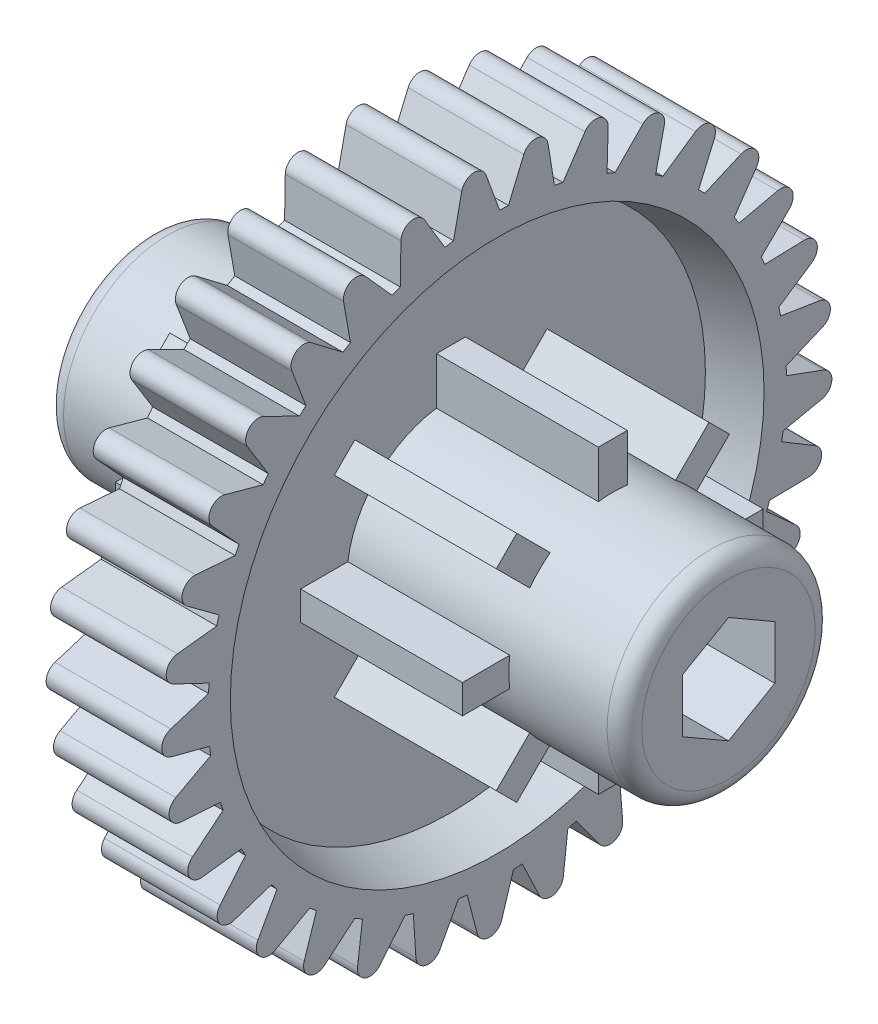
SolidWorks part; units mm, degrees
ref_plane "Front Plane" through (0, 0, 0) normal (0, 0, 1) x (1, 0, 0)
ref_plane "Top Plane" through (0, 0, 0) normal (0, 1, 0) x (1, 0, 0)
ref_plane "Right Plane" through (0, 0, 0) normal (1, 0, 0) x (0, 0, -1)
sketch "Sketch1" plane through (0, 0, 0) normal (1, 0, 0) x (0, 0, -1)
  line L1 (0, -2.3094) -> (2, -1.1547)
  line L2 (2, -1.1547) -> (2, 1.1547)
  line L3 (2, 1.1547) -> (0, 2.3094)
  line L4 (0, 2.3094) -> (-2, 1.1547)
  line L5 (-2, 1.1547) -> (-2, -1.1547)
  line L6 (-2, -1.1547) -> (0, -2.3094)
  circle A0 centre (0, 0) radius 4.5
  circle A1 centre (0, 0) radius 2 construction
  dimension "D1" = 4
  dimension "D2" = 9
extrude "Boss-Extrude1" add sketch "Sketch1" along normal blind 12.5
sketch "Sketch2" plane through (0, 0, 0) normal (1, 0, 0) x (0, 0, -1)
  line L0 (-0.625, 4.4564) -> (-0.625, 6.5)
  line L1 (-0.625, 6.5) -> (0.625, 6.5)
  line L2 (0.625, 6.5) -> (0.625, 4.4564)
  line L3 (2.7092, 3.5931) -> (4.1543, 5.0381)
  line L4 (4.1543, 5.0381) -> (5.0381, 4.1543)
  line L5 (5.0381, 4.1543) -> (3.5931, 2.7092)
  line L6 (4.4564, 0.625) -> (6.5, 0.625)
  line L7 (6.5, 0.625) -> (6.5, -0.625)
  line L8 (6.5, -0.625) -> (4.4564, -0.625)
  line L9 (3.5931, -2.7092) -> (5.0381, -4.1543)
  line L10 (5.0381, -4.1543) -> (4.1543, -5.0381)
  line L11 (4.1543, -5.0381) -> (2.7092, -3.5931)
  line L12 (0.625, -4.4564) -> (0.625, -6.5)
  line L13 (0.625, -6.5) -> (-0.625, -6.5)
  line L14 (-0.625, -6.5) -> (-0.625, -4.4564)
  line L15 (-2.7092, -3.5931) -> (-4.1543, -5.0381)
  line L16 (-4.1543, -5.0381) -> (-5.0381, -4.1543)
  line L17 (-5.0381, -4.1543) -> (-3.5931, -2.7092)
  line L18 (-4.4564, -0.625) -> (-6.5, -0.625)
  line L19 (-6.5, -0.625) -> (-6.5, 0.625)
  line L20 (-6.5, 0.625) -> (-4.4564, 0.625)
  line L21 (-3.5931, 2.7092) -> (-5.0381, 4.1543)
  line L22 (-5.0381, 4.1543) -> (-4.1543, 5.0381)
  line L23 (-4.1543, 5.0381) -> (-2.7092, 3.5931)
  arc A0 (0.625, 4.4564) -> (-0.625, 4.4564) centre (0, 0) ccw
  circle A1 centre (0, 0) radius 4.5 construction
  arc A2 (3.5931, 2.7092) -> (2.7092, 3.5931) centre (0, 0) ccw
  arc A3 (4.4564, -0.625) -> (4.4564, 0.625) centre (0, 0) ccw
  arc A4 (2.7092, -3.5931) -> (3.5931, -2.7092) centre (0, 0) ccw
  arc A5 (-0.625, -4.4564) -> (0.625, -4.4564) centre (0, 0) ccw
  arc A6 (-3.5931, -2.7092) -> (-2.7092, -3.5931) centre (0, 0) ccw
  arc A7 (-4.4564, 0.625) -> (-4.4564, -0.625) centre (0, 0) ccw
  arc A8 (-2.7092, 3.5931) -> (-3.5931, 2.7092) centre (0, 0) ccw
  point P9 (0, 6.5)
  point P37 (0, 0)
  dimension "D2" = 6.5
  dimension "D1" = 1.25
  dimension "D3" = 8
extrude "Boss-Extrude2" add sketch "Sketch2" along normal blind 7.5
sketch "Sketch3" plane through (0, 0, 0) normal (1, 0, 0) x (0, 0, -1)
  circle A0 centre (0, 0) radius 11
  dimension "D1" = 22
extrude "Boss-Extrude3" add sketch "Sketch3" along normal blind 0.5
sketch "Sketch5" plane through (0, 0, 0) normal (1, 0, 0) x (0, 0, -1)
  circle A0 centre (0, 0) radius 11 construction
  circle A1 centre (0, 0) radius 11
  circle A2 centre (0, 0) radius 12.5
  dimension "D1" = 25
extrude "Boss-Extrude4" add sketch "Sketch5" along normal blind 2.5
draft "Draft4" type of draft neutral plane draft angle 15 faces to draft 1 face at (0.5, 0, -11) neutral plane through (0.5, 0, 0) neutral plane normal (1, 0, 0) parameters "D1"=15
sketch "Sketch6" plane through (0, 0, 0) normal (1, 0, 0) x (0, 0, -1)
  line L0 (-9.7582, -7.812) -> (-11.3835, -8.343)
  line L1 (0, 0) -> (-11.3114, -11.3114) construction
  line L2 (-10.8792, -6.1557) -> (-11.9762, -7.4673)
  line L3 (-5.0381, -4.1543) -> (-4.1543, -5.0381) construction
  line L4 (-8.1034, -9.5176) -> (-9.5989, -10.3466)
  line L5 (-9.5176, -8.1034) -> (-10.3466, -9.5989)
  line L6 (0, 0) -> (-13.2477, -8.9663) construction
  line L7 (-11.0603, -5.8241) -> (-12.7567, -6.0379)
  line L8 (-11.8476, -3.9856) -> (-13.173, -5.0659)
  line L9 (0, 0) -> (-14.7051, -6.2971) construction
  line L10 (-11.9626, -3.6257) -> (-13.6689, -3.5145)
  line L11 (-12.3878, -1.6714) -> (-13.8936, -2.4813)
  line L12 (0, 0) -> (-15.6311, -3.4003) construction
  line L13 (-12.4326, -1.2962) -> (-14.087, -0.8642)
  line L14 (-12.4802, 0.7032) -> (-14.1122, 0.1929)
  line L15 (0, 0) -> (-15.9922, -0.3807) construction
  line L16 (-12.4532, 1.0801) -> (-13.996, 1.8174)
  line L17 (-12.1216, 3.0524) -> (-13.8206, 2.8602)
  line L18 (0, 0) -> (-15.7752, 2.6527) construction
  line L19 (-12.0238, 3.4174) -> (-13.3991, 4.4333)
  line L20 (-11.3249, 5.2913) -> (-13.0296, 5.4241)
  line L21 (0, 0) -> (-14.9881, 5.5903) construction
  line L22 (-11.1598, 5.6311) -> (-12.3179, 6.889)
  line L23 (-10.1188, 7.3389) -> (-11.7676, 7.7919)
  line L24 (0, 0) -> (-13.6593, 8.3258) construction
  line L25 (-9.8924, 7.6414) -> (-10.7916, 9.0957)
  line L26 (-8.5471, 9.1213) -> (-10.0803, 9.8781)
  line L27 (0, 0) -> (-11.8368, 10.7603) construction
  line L28 (-8.2675, 9.3754) -> (-8.8752, 10.9737)
  line L29 (-6.6664, 10.574) -> (-8.0287, 11.6073)
  line L30 (0, 0) -> (-9.5865, 12.806) construction
  line L31 (-6.3438, 10.7706) -> (-6.638, 12.455)
  line L32 (-4.5448, 11.6445) -> (-5.6869, 12.917)
  line L33 (0, 0) -> (-6.9897, 14.3889) construction
  line L34 (-4.1908, 11.7766) -> (-4.161, 13.4862)
  line L35 (-2.2589, 12.2942) -> (-3.1396, 13.7598)
  line L36 (0, 0) -> (-4.1403, 15.4516) construction
  line L37 (-1.8863, 12.3569) -> (-1.5335, 14.0299)
  line L38 (0.1086, 12.4995) -> (-0.4788, 14.1054)
  line L39 (0, 0) -> (-1.1412, 15.9559) construction
  line L40 (0.4863, 12.4905) -> (1.1494, 14.0666)
  line L41 (2.4722, 12.2531) -> (2.1993, 13.9411)
  line L42 (0, 0) -> (1.8991, 15.8836) construction
  line L43 (2.8414, 12.1728) -> (3.7908, 13.5949)
  line L44 (4.7464, 11.5638) -> (4.7979, 13.2729)
  line L45 (0, 0) -> (4.8708, 15.2371) construction
  line L46 (5.0937, 11.4151) -> (6.2951, 12.6318)
  line L47 (6.8491, 10.4566) -> (7.2231, 12.125)
  line L48 (0, 0) -> (7.6664, 14.04) construction
  line L49 (7.162, 10.2448) -> (8.5719, 11.2122)
  line L50 (8.7042, 8.9714) -> (9.3873, 10.5389)
  line L51 (0, 0) -> (10.1849, 12.3354) construction
  line L52 (8.9714, 8.7042) -> (10.5389, 9.3873)
  line L53 (10.2448, 7.162) -> (11.2122, 8.5719)
  line L54 (0, 0) -> (12.3354, 10.1849) construction
  line L55 (10.4566, 6.8491) -> (12.125, 7.2231)
  line L56 (11.4151, 5.0937) -> (12.6318, 6.2951)
  line L57 (0, 0) -> (14.04, 7.6664) construction
  line L58 (11.5638, 4.7464) -> (13.2729, 4.7979)
  line L59 (12.1728, 2.8414) -> (13.5949, 3.7908)
  line L60 (0, 0) -> (15.2371, 4.8708) construction
  line L61 (12.2531, 2.4722) -> (13.9411, 2.1993)
  line L62 (12.4905, 0.4863) -> (14.0666, 1.1494)
  line L63 (0, 0) -> (15.8836, 1.8991) construction
  line L64 (12.4995, 0.1086) -> (14.1054, -0.4788)
  line L65 (12.3569, -1.8863) -> (14.0299, -1.5335)
  line L66 (0, 0) -> (15.9559, -1.1412) construction
  line L67 (12.2942, -2.2589) -> (13.7598, -3.1396)
  line L68 (11.7766, -4.1908) -> (13.4862, -4.161)
  line L69 (0, 0) -> (15.4516, -4.1403) construction
  line L70 (11.6445, -4.5448) -> (12.917, -5.6869)
  line L71 (10.7706, -6.3438) -> (12.455, -6.638)
  line L72 (0, 0) -> (14.3889, -6.9897) construction
  line L73 (10.574, -6.6664) -> (11.6073, -8.0287)
  line L74 (9.3754, -8.2675) -> (10.9737, -8.8752)
  line L75 (0, 0) -> (12.806, -9.5865) construction
  line L76 (9.1213, -8.5471) -> (9.8781, -10.0803)
  line L77 (7.6414, -9.8924) -> (9.0957, -10.7916)
  line L78 (0, 0) -> (10.7603, -11.8368) construction
  line L79 (7.3389, -10.1188) -> (7.7919, -11.7676)
  line L80 (5.6311, -11.1598) -> (6.889, -12.3179)
  line L81 (0, 0) -> (8.3258, -13.6593) construction
  line L82 (5.2913, -11.3249) -> (5.4241, -13.0296)
  line L83 (3.4174, -12.0238) -> (4.4333, -13.3991)
  line L84 (0, 0) -> (5.5903, -14.9881) construction
  line L85 (3.0524, -12.1216) -> (2.8602, -13.8206)
  line L86 (1.0801, -12.4532) -> (1.8174, -13.996)
  line L87 (0, 0) -> (2.6527, -15.7752) construction
  line L88 (0.7032, -12.4802) -> (0.1929, -14.1122)
  line L89 (-1.2962, -12.4326) -> (-0.8642, -14.087)
  line L90 (0, 0) -> (-0.3807, -15.9922) construction
  line L91 (-1.6714, -12.3878) -> (-2.4813, -13.8936)
  line L92 (-3.6257, -11.9626) -> (-3.5145, -13.6689)
  line L93 (0, 0) -> (-3.4003, -15.6311) construction
  line L94 (-3.9856, -11.8476) -> (-5.0659, -13.173)
  line L95 (-5.8241, -11.0603) -> (-6.0379, -12.7567)
  line L96 (0, 0) -> (-6.2971, -14.7051) construction
  line L97 (-6.1557, -10.8792) -> (-7.4673, -11.9762)
  line L98 (-7.812, -9.7582) -> (-8.343, -11.3835)
  line L99 (0, 0) -> (-8.9663, -13.2477) construction
  arc A0 (-10.8792, -6.1557) -> (-9.7582, -7.812) centre (0, 0) ccw
  circle A2 centre (0, 0) radius 12.5 construction
  arc A3 (-9.5176, -8.1034) -> (-8.1034, -9.5176) centre (0, 0) ccw
  arc A4 (-9.5989, -10.3466) -> (-10.3466, -9.5989) centre (-9.8655, -9.8655) cw
  arc A5 (-11.3835, -8.343) -> (-11.9762, -7.4673) centre (-11.5543, -7.8202) cw
  arc A6 (-11.8476, -3.9856) -> (-11.0603, -5.8241) centre (0, 0) ccw
  arc A7 (-12.7567, -6.0379) -> (-13.173, -5.0659) centre (-12.8255, -5.4922) cw
  arc A8 (-12.3878, -1.6714) -> (-11.9626, -3.6257) centre (0, 0) ccw
  arc A9 (-13.6689, -3.5145) -> (-13.8936, -2.4813) centre (-13.6331, -2.9657) cw
  arc A10 (-12.4802, 0.7032) -> (-12.4326, -1.2962) centre (0, 0) ccw
  arc A11 (-14.087, -0.8642) -> (-14.1122, 0.1929) centre (-13.948, -0.332) cw
  arc A12 (-12.1216, 3.0524) -> (-12.4532, 1.0801) centre (0, 0) ccw
  arc A13 (-13.996, 1.8174) -> (-13.8206, 2.8602) centre (-13.7588, 2.3137) cw
  arc A14 (-11.3249, 5.2913) -> (-12.0238, 3.4174) centre (0, 0) ccw
  arc A15 (-13.3991, 4.4333) -> (-13.0296, 5.4241) centre (-13.0723, 4.8757) cw
  arc A16 (-10.1188, 7.3389) -> (-11.1598, 5.6311) centre (0, 0) ccw
  arc A17 (-12.3179, 6.889) -> (-11.7676, 7.7919) centre (-11.9133, 7.2616) cw
  arc A18 (-8.5471, 9.1213) -> (-9.8924, 7.6414) centre (0, 0) ccw
  arc A19 (-10.7916, 9.0957) -> (-10.0803, 9.8781) centre (-10.3238, 9.3849) cw
  arc A20 (-6.6664, 10.574) -> (-8.2675, 9.3754) centre (0, 0) ccw
  arc A21 (-8.8752, 10.9737) -> (-8.0287, 11.6073) centre (-8.3611, 11.1691) cw
  arc A22 (-4.5448, 11.6445) -> (-6.3438, 10.7706) centre (0, 0) ccw
  arc A23 (-6.638, 12.455) -> (-5.6869, 12.917) centre (-6.0962, 12.5496) cw
  arc A24 (-2.2589, 12.2942) -> (-4.1908, 11.7766) centre (0, 0) ccw
  arc A25 (-4.161, 13.4862) -> (-3.1396, 13.7598) centre (-3.611, 13.4766) cw
  arc A26 (0.1086, 12.4995) -> (-1.8863, 12.3569) centre (0, 0) ccw
  arc A27 (-1.5335, 14.0299) -> (-0.4788, 14.1054) centre (-0.9953, 13.9164) cw
  arc A28 (2.4722, 12.2531) -> (0.4863, 12.4905) centre (0, 0) ccw
  arc A29 (1.1494, 14.0666) -> (2.1993, 13.9411) centre (1.6564, 13.8533) cw
  arc A30 (4.7464, 11.5638) -> (2.8414, 12.1728) centre (0, 0) ccw
  arc A31 (3.7908, 13.5949) -> (4.7979, 13.2729) centre (4.2482, 13.2895) cw
  arc A32 (6.8491, 10.4566) -> (5.0937, 11.4151) centre (0, 0) ccw
  arc A33 (6.2951, 12.6318) -> (7.2231, 12.125) centre (6.6865, 12.2454) cw
  arc A34 (8.7042, 8.9714) -> (7.162, 10.2448) centre (0, 0) ccw
  arc A35 (8.5719, 11.2122) -> (9.3873, 10.5389) centre (8.8831, 10.7586) cw
  arc A36 (10.2448, 7.162) -> (8.9714, 8.7042) centre (0, 0) ccw
  arc A37 (10.5389, 9.3873) -> (11.2122, 8.5719) centre (10.7586, 8.8831) cw
  arc A38 (11.4151, 5.0937) -> (10.4566, 6.8491) centre (0, 0) ccw
  arc A39 (12.125, 7.2231) -> (12.6318, 6.2951) centre (12.2454, 6.6865) cw
  arc A40 (12.1728, 2.8414) -> (11.5638, 4.7464) centre (0, 0) ccw
  arc A41 (13.2729, 4.7979) -> (13.5949, 3.7908) centre (13.2895, 4.2482) cw
  arc A42 (12.4905, 0.4863) -> (12.2531, 2.4722) centre (0, 0) ccw
  arc A43 (13.9411, 2.1993) -> (14.0666, 1.1494) centre (13.8533, 1.6564) cw
  arc A44 (12.3569, -1.8863) -> (12.4995, 0.1086) centre (0, 0) ccw
  arc A45 (14.1054, -0.4788) -> (14.0299, -1.5335) centre (13.9164, -0.9953) cw
  arc A46 (11.7766, -4.1908) -> (12.2942, -2.2589) centre (0, 0) ccw
  arc A47 (13.7598, -3.1396) -> (13.4862, -4.161) centre (13.4766, -3.611) cw
  arc A48 (10.7706, -6.3438) -> (11.6445, -4.5448) centre (0, 0) ccw
  arc A49 (12.917, -5.6869) -> (12.455, -6.638) centre (12.5496, -6.0962) cw
  arc A50 (9.3754, -8.2675) -> (10.574, -6.6664) centre (0, 0) ccw
  arc A51 (11.6073, -8.0287) -> (10.9737, -8.8752) centre (11.1691, -8.3611) cw
  arc A52 (7.6414, -9.8924) -> (9.1213, -8.5471) centre (0, 0) ccw
  arc A53 (9.8781, -10.0803) -> (9.0957, -10.7916) centre (9.3849, -10.3238) cw
  arc A54 (5.6311, -11.1598) -> (7.3389, -10.1188) centre (0, 0) ccw
  arc A55 (7.7919, -11.7676) -> (6.889, -12.3179) centre (7.2616, -11.9133) cw
  arc A56 (3.4174, -12.0238) -> (5.2913, -11.3249) centre (0, 0) ccw
  arc A57 (5.4241, -13.0296) -> (4.4333, -13.3991) centre (4.8757, -13.0723) cw
  arc A58 (1.0801, -12.4532) -> (3.0524, -12.1216) centre (0, 0) ccw
  arc A59 (2.8602, -13.8206) -> (1.8174, -13.996) centre (2.3137, -13.7588) cw
  arc A60 (-1.2962, -12.4326) -> (0.7032, -12.4802) centre (0, 0) ccw
  arc A61 (0.1929, -14.1122) -> (-0.8642, -14.087) centre (-0.332, -13.948) cw
  arc A62 (-3.6257, -11.9626) -> (-1.6714, -12.3878) centre (0, 0) ccw
  arc A63 (-2.4813, -13.8936) -> (-3.5145, -13.6689) centre (-2.9657, -13.6331) cw
  arc A64 (-5.8241, -11.0603) -> (-3.9856, -11.8476) centre (0, 0) ccw
  arc A65 (-5.0659, -13.173) -> (-6.0379, -12.7567) centre (-5.4922, -12.8255) cw
  arc A66 (-7.812, -9.7582) -> (-6.1557, -10.8792) centre (0, 0) ccw
  arc A67 (-7.4673, -11.9762) -> (-8.343, -11.3835) centre (-7.8202, -11.5543) cw
  point P205 (0, 0)
  dimension "D1" = 2
  dimension "D3" = 16
  dimension "D2" = 0.55
  dimension "D4" = 33
extrude "Boss-Extrude5" add sketch "Sketch6" along normal up to surface (2.5 mm away) up to face at (2.5, 0, -12.5)
fillet "Fillet1" radius 0.75 1 edges at (12.5, 0, -4.5)
sketch "Sketch7" plane through (12.5, 0, 0) normal (1, 0, 0) x (0, 0, -1)
  line L0 (2, 1.1547) -> (0, 2.3094) construction
  line L1 (0, 2.3094) -> (-2, 1.1547) construction
  line L2 (-2, 1.1547) -> (-2, -1.1547) construction
  line L3 (-2, -1.1547) -> (0, -2.3094) construction
  line L4 (0, -2.3094) -> (2, -1.1547) construction
  line L5 (2, -1.1547) -> (2, 1.1547) construction
  line L6 (2, 1.1547) -> (0, 2.3094)
  line L7 (0, 2.3094) -> (-2, 1.1547)
  line L8 (-2, 1.1547) -> (-2, -1.1547)
  line L9 (-2, -1.1547) -> (0, -2.3094)
  line L10 (0, -2.3094) -> (2, -1.1547)
  line L11 (2, -1.1547) -> (2, 1.1547)
extrude "Cut-Extrude1" cut sketch "Sketch7" against normal through all
mirror "Mirror1" about plane through (0, 0, 0) normal (1, 0, 0) of bodies 106
